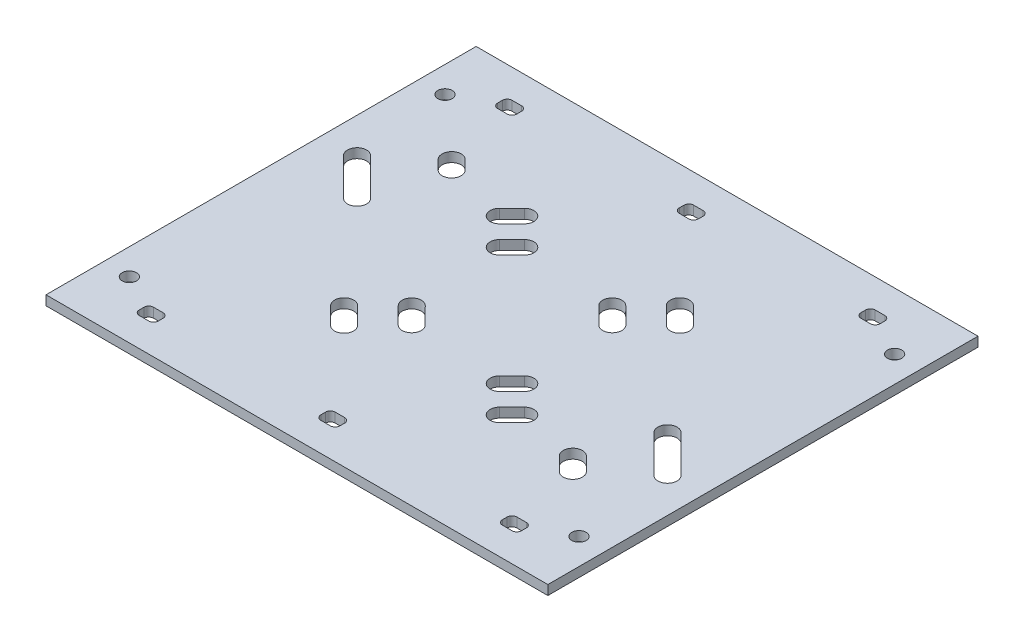
SolidWorks part; units mm, degrees
ref_plane "Front Plane" through (0, 0, 0) normal (0, 0, 1) x (1, 0, 0)
ref_plane "Top Plane" through (0, 0, 0) normal (0, 1, 0) x (1, 0, 0)
ref_plane "Right Plane" through (0, 0, 0) normal (1, 0, 0) x (0, 0, -1)
sketch "Sketch1" plane through (0, 0, 0) normal (0, 1, 0) x (1, 0, 0)
  line L1 (0, 0) -> (105, 0)
  line L2 (0, 0) -> (0, 90)
  line L3 (0, 90) -> (105, 90)
  line L4 (105, 0) -> (105, 90)
  dimension "D1" = 105
  dimension "D2" = 90
extrude "Boss-Extrude1" add sketch "Sketch1" along normal blind 2
hole_wizard "M3 Clearance Hole1" positions "Sketch3" profile "Sketch2" hole size "M3" standard "ANSI Metric"
sketch "Sketch3" plane through (0, 2, 0) normal (0, 1, 0) x (1, 0, 0)
  line L0 (0, 90) -> (0, 0) construction
  line L1 (105, 0) -> (105, 90) construction
  line L2 (0, 0) -> (105, 0) construction
  line L3 (105, 90) -> (0, 90) construction
  point P0 (5.46, 11.98)
  point P2 (5.46, 78.02)
  point P4 (99.54, 78.02)
  point P6 (99.54, 11.98)
  dimension "D1" = 66.04
  dimension "D2" = 66.04
  dimension "D3" = 94.08
  dimension "D4" = 94.08
  dimension "D5" = 5.46
  dimension "D6" = 5.46
  dimension "D7" = 11.98
  dimension "D8" = 11.98
  dimension "D9" = 11.98
  dimension "D10" = 11.98
  dimension "D11" = 5.46
sketch "Sketch2" plane through (5.46, 2, -11.98) normal (1, 0, 0) x (0, 0, 1)
  line L0 (0, 0) -> (0, 2.9013)
  line L1 (0, 2.9013) -> (1.5, 2)
  line L2 (1.5, 2) -> (1.5, 0)
  line L5 (1.5, 0) -> (0, 0)
  line L10 (0, 2.9013) -> (-1.5, 2) construction
  line L11 (0, -6.35) -> (0, 107.95) construction
  dimension "Hole Dia." = 3
  dimension "Hole Depth" = 2
  dimension "Drill Angle" = 118
sketch "Sketch4" plane through (0, 2, 0) normal (0, 1, 0) x (1, 0, 0)
  line L0 (0, 90) -> (0, 0) construction
  line L1 (12.5, 81) -> (16.5, 81)
  line L2 (12.5, 81) -> (12.5, 84)
  line L3 (12.5, 84) -> (16.5, 84)
  line L4 (16.5, 81) -> (16.5, 84)
  line L5 (105, 90) -> (0, 90) construction
  dimension "D1" = 3
  dimension "D2" = 4
  dimension "D3" = 12.5
  dimension "D4" = 6
extrude "Cut-Extrude1" cut sketch "Sketch4" against normal through all
fillet "Fillet1" radius 1 1 edges at (12.5, 1, -84)
fillet "Fillet2" radius 1 1 edges at (12.5, 1, -81)
fillet "Fillet3" radius 1 1 edges at (16.5, 1, -84)
fillet "Fillet4" radius 1 1 edges at (16.5, 1, -81)
pattern_linear "LPattern1" count 2 spacing 75 along (0, 0, 1) count 3 spacing 38 along (1, 0, 0) of "Cut-Extrude1", "Fillet1", "Fillet2", "Fillet3", "Fillet4"
sketch "Sketch6" plane through (0, 0, 0) normal (0, -1, 0) x (1, 0, 0)
  line L0 (33.1424, -29.2371) -> (36.7407, -25.6303) construction
  line L3 (31.7265, -27.8246) -> (35.3248, -24.2178)
  line L4 (34.5582, -30.6497) -> (38.1566, -27.0429)
  line L6 (43.729, -32.7844) -> (40.2425, -36.279) construction
  line L7 (45.1448, -34.197) -> (41.6584, -37.6916)
  line L8 (42.3131, -31.3719) -> (38.8267, -34.8665)
  line L11 (87.8553, -9.6453) -> (17.1447, -80.356) construction
  line L12 (52.5, 25.71) -> (123.2107, -45.0007) construction
  line L13 (52.5, -115.7114) -> (-18.2107, -45.0007) construction
  line L14 (68.2636, -64.3583) -> (71.8703, -60.76) construction
  line L15 (69.6761, -65.7742) -> (73.2829, -62.1759)
  line L16 (66.851, -62.9424) -> (70.4578, -59.3441)
  line L17 (64.7163, -53.7717) -> (61.2216, -57.2581) construction
  line L18 (63.3037, -52.3558) -> (59.8091, -55.8423)
  line L19 (66.1288, -55.1876) -> (62.6342, -58.674)
  line L20 (15.0786, -50.0057) -> (7.3005, -57.7839) construction
  line L21 (97.7548, -32.2728) -> (89.9767, -40.0509) construction
  line L22 (99.169, -33.687) -> (91.3909, -41.4651)
  line L23 (96.3406, -30.8585) -> (88.5624, -38.6367)
  line L24 (16.4929, -51.4199) -> (8.7147, -59.1981)
  line L25 (13.6644, -48.5915) -> (5.8863, -56.3697)
  line L26 (17.9071, -66.9763) -> (19.87, -65.0134) construction
  line L27 (31.6569, -80.7262) -> (16.7745, -65.8437) construction
  line L28 (16.4929, -65.5621) -> (18.4558, -63.5992)
  line L29 (19.3213, -68.3905) -> (21.2842, -66.4276)
  line L30 (87.1482, -23.0804) -> (84.3198, -25.9088) construction
  line L31 (73.3431, -9.2752) -> (88.2255, -24.1576) construction
  line L32 (88.5624, -24.4946) -> (85.734, -27.323)
  line L33 (85.734, -21.6662) -> (82.9056, -24.4946)
  line L34 (17.1447, -9.6453) -> (87.8553, -80.356) construction
  line L35 (-18.2107, -45.0007) -> (52.5, 25.71) construction
  line L36 (123.2107, -45.0007) -> (52.5, -115.7114) construction
  line L37 (33.2042, -61.7267) -> (35.774, -64.2965) construction
  line L38 (17.3308, -64.1481) -> (34.8921, -61.4692) construction
  line L39 (36.0315, -62.6086) -> (33.3526, -80.1699) construction
  line L40 (34.6184, -60.3125) -> (37.1882, -62.8823)
  line L41 (31.7899, -63.1409) -> (34.3598, -65.7107)
  line L42 (38.864, -56.0729) -> (41.4308, -58.6397) construction
  line L43 (69.226, -25.7048) -> (71.7958, -28.2747) construction
  line L44 (67.8118, -27.119) -> (70.3816, -29.6889)
  line L45 (40.2782, -54.6587) -> (42.845, -57.2255)
  line L46 (37.4498, -57.4871) -> (40.0166, -60.0539)
  line L47 (70.6402, -24.2906) -> (73.2101, -26.8604)
  line L48 (63.5722, -31.3647) -> (66.139, -33.9315) construction
  line L49 (62.158, -32.7789) -> (64.7248, -35.3457)
  line L50 (64.9864, -29.9505) -> (67.5532, -32.5173)
  arc A0 (31.7265, -27.8246) -> (34.5582, -30.6497) centre (33.1424, -29.2371) ccw
  arc A1 (38.1566, -27.0429) -> (35.3248, -24.2178) centre (36.7407, -25.6303) ccw
  arc A2 (45.1448, -34.197) -> (42.3131, -31.3719) centre (43.729, -32.7844) ccw
  arc A3 (38.8267, -34.8665) -> (41.6584, -37.6916) centre (40.2425, -36.279) ccw
  arc A4 (69.6761, -65.7742) -> (66.851, -62.9424) centre (68.2636, -64.3583) cw
  arc A5 (70.4578, -59.3441) -> (73.2829, -62.1759) centre (71.8703, -60.76) cw
  arc A6 (63.3037, -52.3558) -> (66.1288, -55.1876) centre (64.7163, -53.7717) cw
  arc A7 (62.6342, -58.674) -> (59.8091, -55.8423) centre (61.2216, -57.2581) cw
  arc A9 (99.169, -33.687) -> (96.3406, -30.8585) centre (97.7548, -32.2728) ccw
  arc A10 (88.5624, -38.6367) -> (91.3909, -41.4651) centre (89.9767, -40.0509) ccw
  arc A11 (88.5624, -38.6367) -> (91.3909, -41.4651) centre (89.9767, -40.0509) ccw construction
  arc A12 (16.4929, -51.4199) -> (13.6644, -48.5915) centre (15.0786, -50.0057) ccw
  arc A13 (5.8863, -56.3697) -> (8.7147, -59.1981) centre (7.3005, -57.7839) ccw
  arc A14 (16.4929, -65.5621) -> (19.3213, -68.3905) centre (17.9071, -66.9763) ccw
  arc A15 (21.2842, -66.4276) -> (18.4558, -63.5992) centre (19.87, -65.0134) ccw
  arc A16 (88.5624, -24.4946) -> (85.734, -21.6662) centre (87.1482, -23.0804) ccw
  arc A17 (82.9056, -24.4946) -> (85.734, -27.323) centre (84.3198, -25.9088) ccw
  arc A18 (34.6184, -60.3125) -> (31.7899, -63.1409) centre (33.2042, -61.7267) ccw
  arc A19 (34.3598, -65.7107) -> (37.1882, -62.8823) centre (35.774, -64.2965) ccw
  arc A20 (40.2782, -54.6587) -> (37.4498, -57.4871) centre (38.864, -56.0729) ccw
  arc A21 (40.0166, -60.0539) -> (42.845, -57.2255) centre (41.4308, -58.6397) ccw
  arc A22 (67.8118, -27.119) -> (70.6402, -24.2906) centre (69.226, -25.7048) cw
  arc A23 (73.2101, -26.8604) -> (70.3816, -29.6889) centre (71.7958, -28.2747) cw
  arc A24 (62.158, -32.7789) -> (64.9864, -29.9505) centre (63.5722, -31.3647) cw
  arc A25 (67.5532, -32.5173) -> (64.7248, -35.3457) centre (66.139, -33.9315) cw
  point P6 (34.9415, -27.4337)
  point P15 (41.9857, -34.5317)
  point P34 (70.0669, -62.5591)
  point P41 (62.969, -55.5149)
  point P50 (93.8657, -36.1618)
  point P58 (88.5624, -41.4651)
  point P62 (11.1896, -53.8948)
  point P73 (18.8885, -65.9948)
  point P82 (85.734, -24.4946)
  point P99 (34.4891, -63.0116)
  point P108 (70.5109, -26.9897)
  point P110 (40.1474, -57.3563)
  point P120 (64.8556, -32.6481)
  dimension "D7" = 2
  dimension "D10" = 9
  dimension "D11" = 10
  dimension "D14" = 4
  dimension "D2" = 4
  dimension "D3" = 10
  dimension "D4" = 4
  dimension "D8" = 4
  dimension "D9" = 10
  dimension "D12" = 4
  dimension "D13" = 4
  dimension "D15" = 4
  dimension "D16" = 3.63
  dimension "D17" = 3.6343
  dimension "D18" = 8
extrude "Cut-Extrude2" cut sketch "Sketch6" against normal through all
